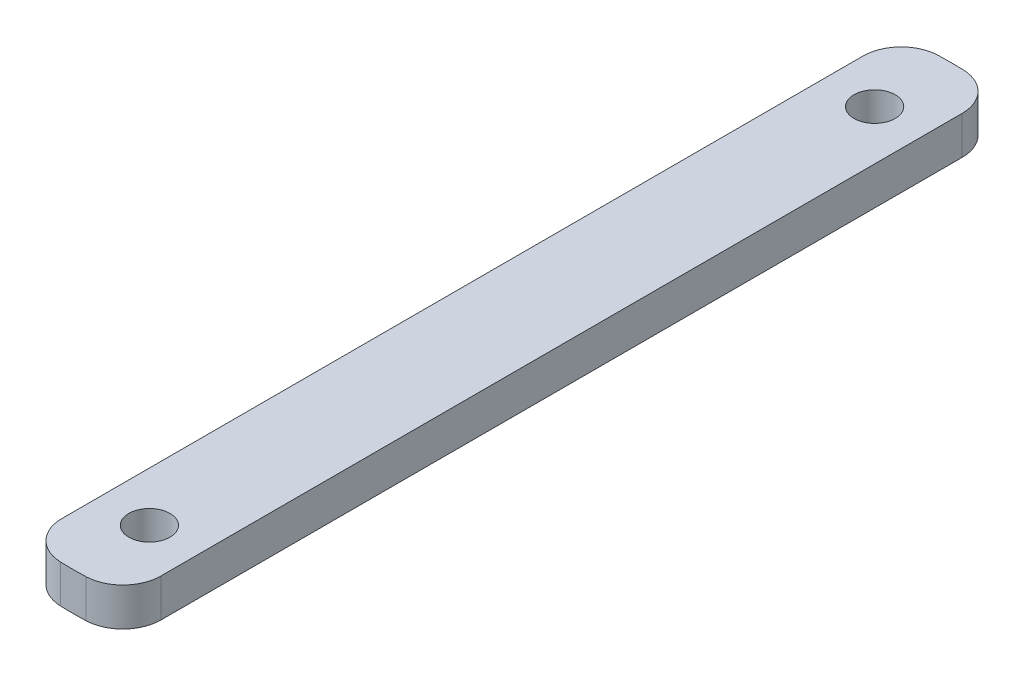
SolidWorks part; units mm, degrees
material "1023 Carbon Steel Sheet (SS)"
ref_plane "Front Plane" through (0, 0, 0) normal (0, 0, 1) x (1, 0, 0)
ref_plane "Top Plane" through (0, 0, 0) normal (0, 1, 0) x (1, 0, 0)
ref_plane "Right Plane" through (0, 0, 0) normal (1, 0, 0) x (0, 0, -1)
sketch "Sketch1" plane through (0, 0, 0) normal (0, 1, 0) x (1, 0, 0)
  line L0 (0, 0) -> (0, 60.325) construction
  line L1 (0, 0) -> (73.025, 0) construction
  circle A0 centre (0, 0) radius 73.025
  circle A1 centre (0, 60.325) radius 3.429
  circle A2 centre (0, -60.325) radius 3.429
  dimension "D2" = 146.05
  dimension "D3" = 6.858
  dimension "D1" = 120.65
extrude "Boss-Extrude1" add sketch "Sketch1" along normal blind 6.35
sketch "Sketch2" plane through (0, 6.35, 0) normal (0, 1, 0) x (1, 0, 0)
  line L0 (0, 0) -> (0, 73.025) construction
  line L1 (0, 73.025) -> (8.255, 73.025) construction
  line L2 (0, 0) -> (8.255, 0) construction
  line L3 (8.255, 73.025) -> (73.025, 73.025)
  line L4 (8.255, 73.025) -> (8.255, -73.025)
  line L6 (73.025, 73.025) -> (73.025, -73.025)
  line L7 (8.255, 0) -> (73.025, 0) construction
  line L8 (8.255, -73.025) -> (73.025, -73.025)
  line L9 (-8.255, 0) -> (-73.025, 0) construction
  line L10 (-8.255, -73.025) -> (-73.025, -73.025)
  line L11 (-73.025, 73.025) -> (-73.025, -73.025)
  line L12 (-8.255, 73.025) -> (-8.255, -73.025)
  line L13 (-8.255, 73.025) -> (-73.025, 73.025)
  circle A0 centre (0, 0) radius 73.025 construction
  dimension "D1" = 16.51
extrude "Cut-Extrude1" cut sketch "Sketch2" against normal through all
fillet "Fillet1" radius 6.35 4 edges at (-8.255, 3.175, -72.5569) (-8.255, 3.175, 72.5569) (8.255, 3.175, 72.5569) (8.255, 3.175, -72.5569)
sketch "Sketch3" [suppressed] plane through (0, 6.35, 0) normal (0, 1, 0) x (1, 0, 0)
  line L0 (0, 60.325) -> (0, -60.325) construction
  line L1 (0, 60.325) -> (8.255, 66.6478) construction
  line L2 (0, 60.325) -> (8.255, 54.0022) construction
  line L3 (8.255, 66.6478) -> (8.255, -66.6478) construction
  line L4 (0, 0) -> (8.255, 0) construction
  line L5 (8.255, 66.6478) -> (8.255, 54.0022) construction
  line L6 (2.032, 38.9786) -> (2.032, -38.9786)
  line L7 (8.255, 54.0022) -> (8.255, -54.0022)
  line L8 (5.1435, 46.4904) -> (8.255, 49.6019) construction
  line L9 (8.255, 54.0022) -> (8.255, -54.0022)
  line L10 (5.1435, -46.4904) -> (8.255, -49.6019) construction
  line L11 (-5.1435, -46.4904) -> (-8.255, -49.6019) construction
  line L12 (-5.1435, 46.4904) -> (-8.255, 49.6019) construction
  line L13 (-8.255, 54.0022) -> (-8.255, -54.0022)
  line L14 (-8.255, 54.0022) -> (-8.255, -54.0022)
  line L15 (-2.032, 38.9786) -> (-2.032, -38.9786)
  line L16 (0, 60.325) -> (-8.255, 54.0022) construction
  arc A0 (8.255, 54.0022) -> (5.1435, 46.4904) centre (-2.3683, 54.0022) cw
  arc A1 (5.1435, 46.4904) -> (2.032, 38.9786) centre (12.6553, 38.9786) ccw
  arc A2 (5.1435, -46.4904) -> (2.032, -38.9786) centre (12.6553, -38.9786) cw
  arc A3 (8.255, -54.0022) -> (5.1435, -46.4904) centre (-2.3683, -54.0022) ccw
  arc A4 (-8.255, -54.0022) -> (-5.1435, -46.4904) centre (2.3683, -54.0022) cw
  arc A5 (-5.1435, -46.4904) -> (-2.032, -38.9786) centre (-12.6553, -38.9786) ccw
  arc A6 (-5.1435, 46.4904) -> (-2.032, 38.9786) centre (-12.6553, 38.9786) cw
  arc A7 (-8.255, 54.0022) -> (-5.1435, 46.4904) centre (2.3683, 54.0022) ccw
  point P24 (2.032, 0)
  point P36 (-2.032, 0)
  line M9 (-8.255, 66.6478) -> (-8.255, -66.6478)
  line M13 (8.255, -66.6478) -> (8.255, 66.6478)
  dimension "D1" = 6.223
  dimension "D2" = 45
extrude "Cut-Extrude2" [suppressed] cut sketch "Sketch3" against normal through all contours A3 A0 A1 L6 A2 M13 | A7 A4 A5 L15 A6 M9
equation "\"width\"= 0.65"
equation "\"D1@Sketch2\"=\"width\""
